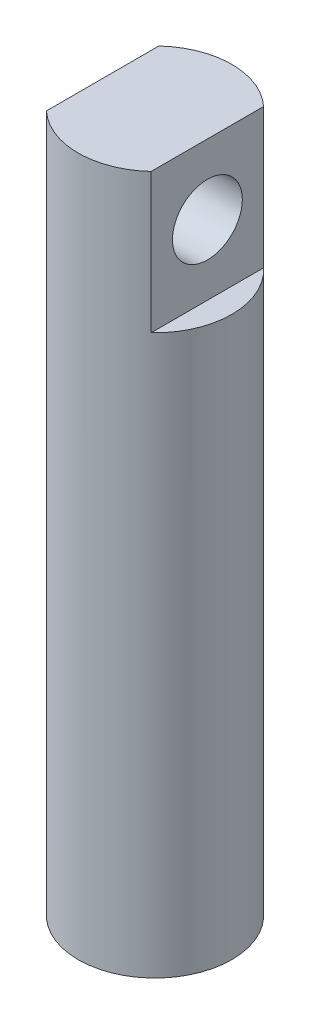
SolidWorks part; units mm, degrees
ref_plane "Front Plane" through (0, 0, 0) normal (0, 0, 1) x (1, 0, 0)
ref_plane "Top Plane" through (0, 0, 0) normal (0, 1, 0) x (1, 0, 0)
ref_plane "Right Plane" through (0, 0, 0) normal (1, 0, 0) x (0, 0, -1)
sketch "Sketch1" plane through (0, 0, 0) normal (0, 1, 0) x (1, 0, 0)
  circle A0 centre (0, 0) radius 4.4
  dimension "D1" = 8.8
extrude "Boss-Extrude1" add sketch "Sketch1" along normal blind 40
sketch "Sketch2" plane through (0, 40, 0) normal (0, 1, 0) x (1, 0, 0)
  line L1 (-5.8, -3.2187) -> (-3, -3.2187)
  line L2 (-5.8, -3.2187) -> (-5.8, 3.2187)
  line L3 (-5.8, 3.2187) -> (-3, 3.2187)
  line L4 (-3, -3.2187) -> (-3, 3.2187)
  line L5 (-5.8, -3.2187) -> (-3, 3.2187) construction
  line L6 (-5.8, 3.2187) -> (-3, -3.2187) construction
  line L7 (5.8, -3.2187) -> (3, -3.2187)
  line L8 (5.8, -3.2187) -> (5.8, 3.2187)
  line L9 (5.8, 3.2187) -> (3, 3.2187)
  line L10 (3, -3.2187) -> (3, 3.2187)
  line L11 (5.8, -3.2187) -> (3, 3.2187) construction
  line L12 (5.8, 3.2187) -> (3, -3.2187) construction
  circle A0 centre (0, 0) radius 4.4 construction
  point P0 (-4.4, 0)
  point P7 (4.4, 0)
  point P12 (3, -3.2187)
  point P13 (0, 0)
  point P14 (-3, -3.2187)
  dimension "D1" = 6
extrude "Cut-Extrude1" cut sketch "Sketch2" against normal blind 8
sketch "Sketch3" plane through (3, 0, 0) normal (1, 0, 0) x (0, 0, -1)
  line L0 (0, 40) -> (0, 36) construction
  line L1 (3.2187, 40) -> (-3.2187, 40) construction
  circle A0 centre (0, 36) radius 2
  dimension "D1" = 4
  dimension "D2" = 4
extrude "Cut-Extrude2" cut sketch "Sketch3" against normal through all
